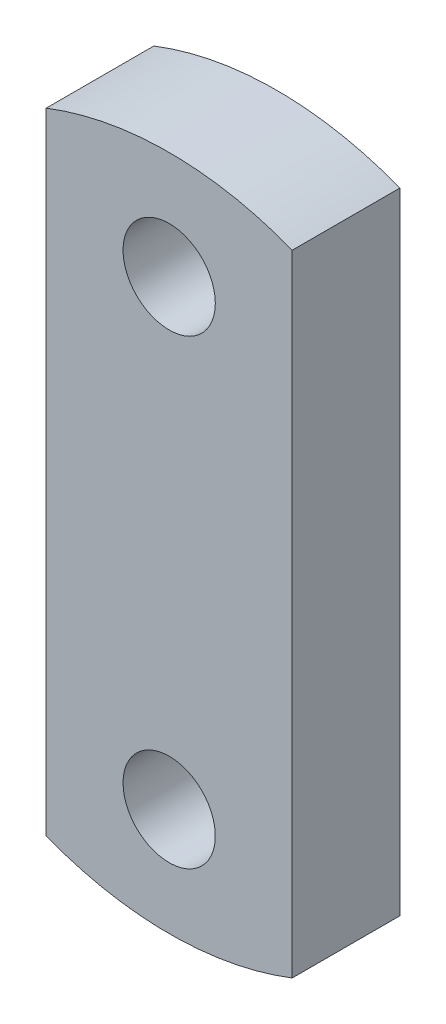
SolidWorks part; units mm, degrees
ref_plane "Front Plane" through (0, 0, 0) normal (0, 0, 1) x (1, 0, 0)
ref_plane "Top Plane" through (0, 0, 0) normal (0, 1, 0) x (1, 0, 0)
ref_plane "Right Plane" through (0, 0, 0) normal (1, 0, 0) x (0, 0, -1)
sketch "Sketch1" plane through (0, 0, 0) normal (0, 0, 1) x (1, 0, 0)
  line L0 (0, 110) -> (0, -110) construction
  line L1 (66.9074, 0) -> (-63.1375, 0) construction
  line L2 (-40, 102.4695) -> (-40, -102.4695)
  line L3 (40, 102.4695) -> (40, -102.4695)
  arc A0 (40, 102.4695) -> (-40, 102.4695) centre (0, 0) ccw
  circle A1 centre (0, 75) radius 15
  circle A3 centre (0, -75) radius 15
  arc A4 (-40, -102.4695) -> (40, -102.4695) centre (0, 0) ccw
  point P1 (38.152, -102.4695)
  dimension "D1" = 220
  dimension "D2" = 30
  dimension "D3" = 150
  dimension "D4" = 40
  dimension "D5" = 40
extrude "Boss-Extrude2" add sketch "Sketch1" along normal blind 35
